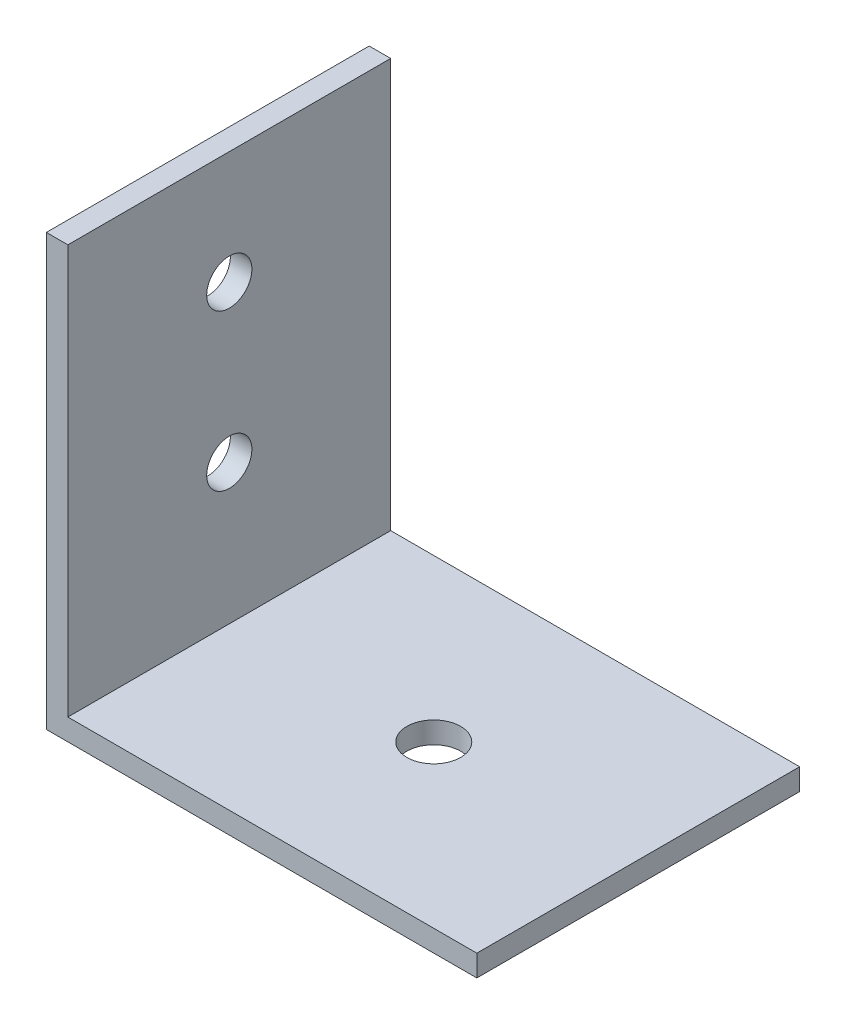
SolidWorks part; units mm, degrees
material "1060 Alloy"
ref_plane "Front Plane" through (0, 0, 0) normal (0, 0, 1) x (1, 0, 0)
ref_plane "Top Plane" through (0, 0, 0) normal (0, 1, 0) x (1, 0, 0)
ref_plane "Right Plane" through (0, 0, 0) normal (1, 0, 0) x (0, 0, -1)
sketch "Sketch1" plane through (0, 0, 0) normal (0, 0, 1) x (1, 0, 0)
  line L0 (-8, 5) -> (-8, -33)
  line L2 (-10, 5) -> (-10, -35)
  line L3 (-10, -35) -> (30, -35)
  line L5 (-8, -33) -> (30, -33)
  line L6 (-10, 5) -> (-8, 5)
  line L7 (30, -33) -> (30, -35)
  point P0 (0, 0)
  dimension "D1" = 40
  dimension "D2" = 40
  dimension "D3" = 2
extrude "Boss-Extrude1" add sketch "Sketch1" along normal blind 30
sketch "Sketch2" plane through (-8, 0, 0) normal (1, 0, 0) x (0, 0, -1)
  line L2 (-30, 5) -> (0, 5) construction
  line L3 (-15, -35) -> (-15, 5) construction
  line L4 (-30, -35) -> (0, -35) construction
  line L5 (-30, 5) -> (0, 5) construction
  circle A0 centre (-15, -5.5) radius 2.1
  circle A1 centre (-15, -20) radius 2.1
  dimension "D1" = 4.2
  dimension "D2" = 4.2
  dimension "D5" = 10.5
  dimension "D6" = 25
extrude "Cut-Extrude1" cut sketch "Sketch2" against normal blind 30
sketch "Sketch3" plane through (0, -33, 0) normal (0, 1, 0) x (1, 0, 0)
  line L0 (11, -30) -> (11, 0) construction
  line L1 (30, -30) -> (-8, -30) construction
  line L2 (30, 0) -> (-8, 0) construction
  circle A0 centre (11, -15) radius 2.5
  dimension "D1" = 5
extrude "Cut-Extrude2" cut sketch "Sketch3" against normal blind 10
